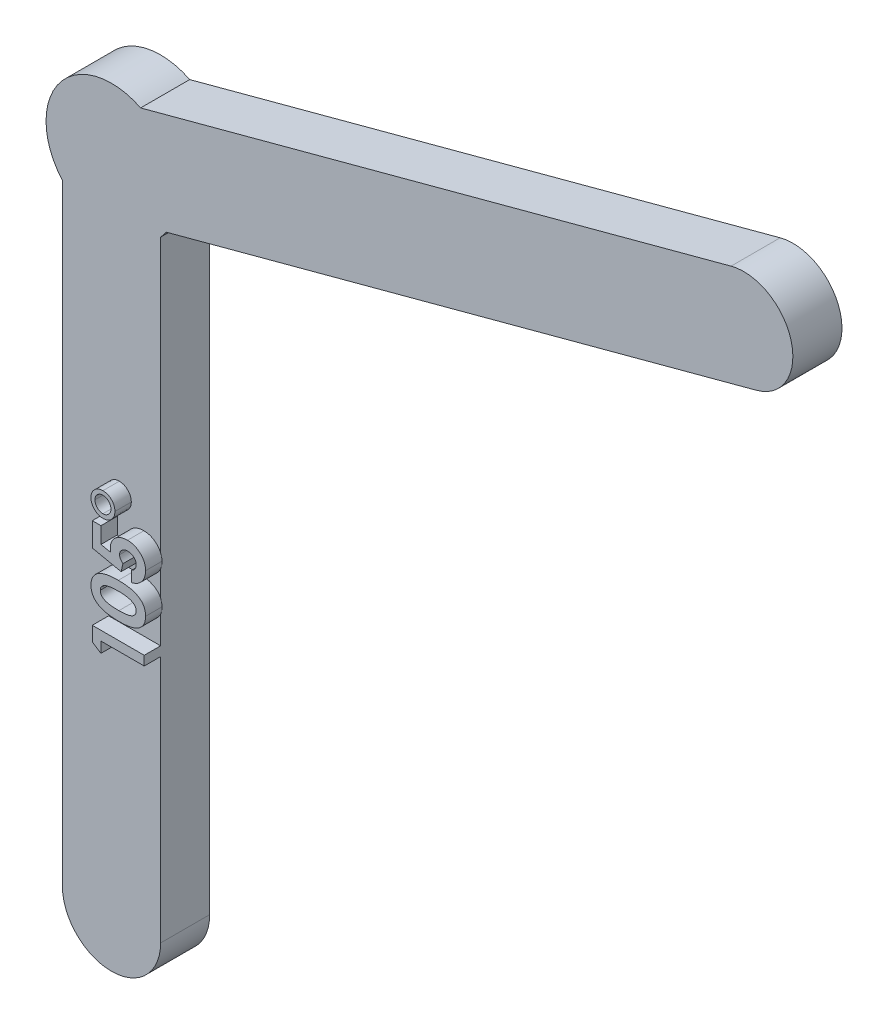
SolidWorks part; units mm, degrees
ref_plane "Front Plane" through (0, 0, 0) normal (0, 0, 1) x (1, 0, 0)
ref_plane "Top Plane" through (0, 0, 0) normal (0, 1, 0) x (1, 0, 0)
ref_plane "Right Plane" through (0, 0, 0) normal (1, 0, 0) x (0, 0, -1)
sketch "Sketch2" plane through (0, 0, 0) normal (0, 0, 1) x (1, 0, 0)
  line L0 (0, 0) -> (0, -40) construction
  line L1 (0, 0) -> (38.637, 10.3528) construction
  line L2 (37.8606, 13.2505) -> (39.4135, 7.455) construction
  line L3 (-3, -40) -> (3, -40) construction
  line L4 (-3, -40) -> (-3, -2.6458)
  line L5 (3, -40) -> (3, -2.6458)
  line L6 (37.8606, 13.2505) -> (1.7791, 3.5825)
  line L7 (39.4135, 7.455) -> (3.3321, -2.213)
  arc A0 (1.7791, 3.5825) -> (-3, -2.6458) centre (0, 0) ccw
  arc A1 (-3, -40) -> (3, -40) centre (0, -40) ccw
  arc A2 (37.8606, 13.2505) -> (39.4135, 7.455) centre (38.637, 10.3528) cw
  arc A3 (3, -2.6458) -> (3.3321, -2.213) centre (0, 0) ccw
  point P12 (38.637, 10.3528)
  dimension "D3" = 3
  dimension "D4" = 8
  dimension "D1" = 40
  dimension "D2" = 105
extrude "Boss-Extrude1" add sketch "Sketch2" along normal blind 3
sketch "Sketch3" plane through (0, 0, 3) normal (0, 0, 1) x (1, 0, 0)
  text T0 "<b>105°</b>"
extrude "Boss-Extrude2" add sketch "Sketch3" along normal blind 1
